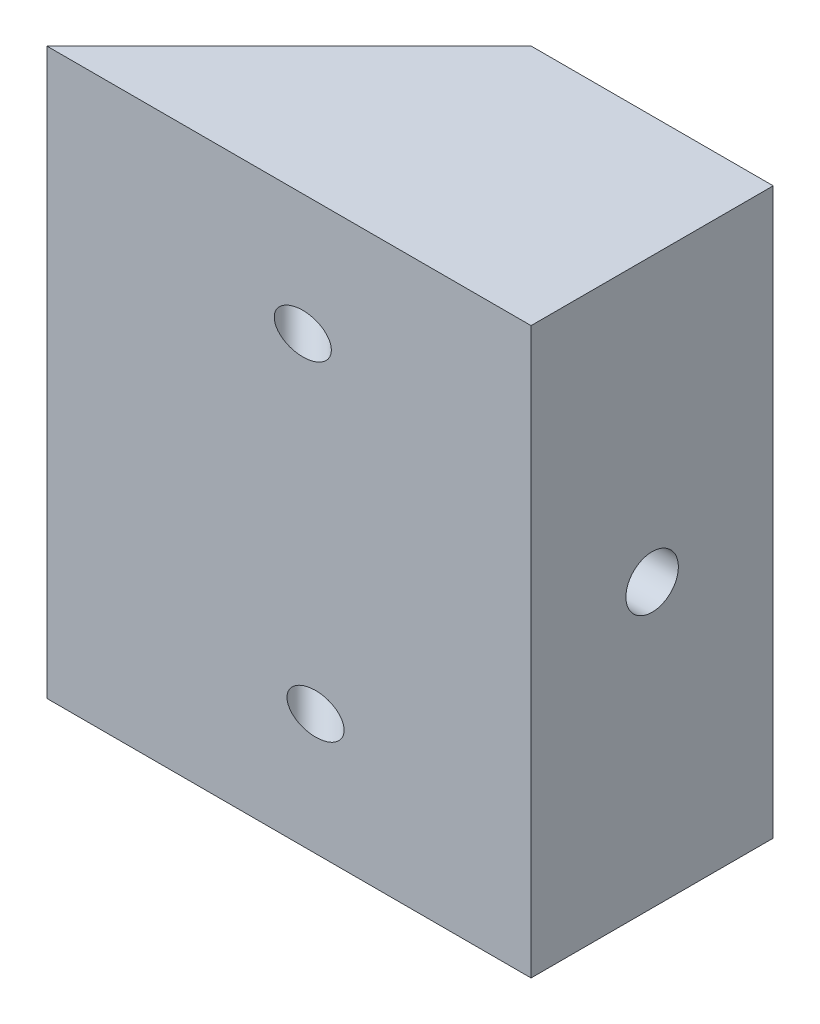
SolidWorks part; units mm, degrees
ref_plane "Front Plane" through (0, 0, 0) normal (0, 0, 1) x (1, 0, 0)
ref_plane "Top Plane" through (0, 0, 0) normal (0, 1, 0) x (1, 0, 0)
ref_plane "Right Plane" through (0, 0, 0) normal (1, 0, 0) x (0, 0, -1)
sketch "Sketch1" plane through (0, 0, 0) normal (0, 1, 0) x (1, 0, 0)
  line L0 (0, 0) -> (38.1, 38.1)
  line L1 (38.1, 38.1) -> (76.2, 38.1)
  line L2 (76.2, 38.1) -> (76.2, 0)
  line L3 (76.2, 0) -> (0, 0)
  dimension "D1" = 135
  dimension "D2" = 38.1
  dimension "D3" = 76.2
extrude "Boss-Extrude1" add sketch "Sketch1" along normal blind 88.9
ref_plane "Plane1" through (38.1, 0, 38.1) normal (-0.7071, 0, -0.7071) x (-0.7071, 0, 0.7071)
sketch "Sketch2" plane through (38.1, 0, 38.1) normal (-0.7071, 0, -0.7071) x (-0.7071, 0, 0.7071)
  line L0 (0, 88.9) -> (-53.8815, 88.9) construction
  line L1 (0, 0) -> (-53.8815, 0) construction
  line L2 (-53.8815, 88.9) -> (-53.8815, 0) construction
  circle A0 centre (-28.4815, 69.85) radius 3.175
  circle A1 centre (-29.9018, 19.05) radius 3.175
  dimension "D1" = 6.35
  dimension "D2" = 19.05
  dimension "D3" = 19.05
  dimension "D4" = 25.4
extrude "Cut-Extrude1" cut sketch "Sketch2" along normal blind 38.1
sketch "Sketch3" plane through (76.2, 0, 0) normal (1, 0, 0) x (0, 0, -1)
  line L0 (0, 88.9) -> (0, 0) construction
  line L1 (0, 0) -> (38.1, 0) construction
  circle A0 centre (19.05, 44.45) radius 4.1275
  dimension "D1" = 8.255
  dimension "D2" = 19.05
  dimension "D3" = 44.45
extrude "Cut-Extrude2" cut sketch "Sketch3" against normal blind 25.4
